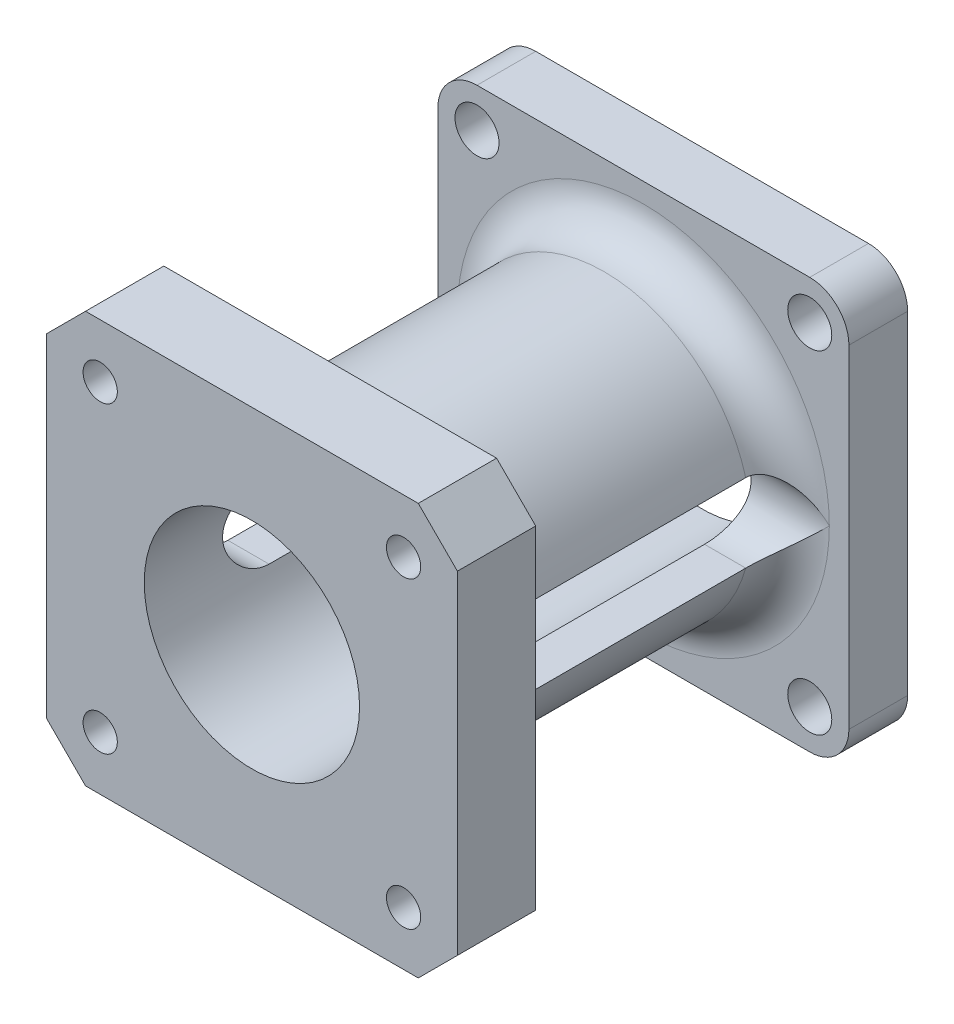
SolidWorks part; units mm, degrees
ref_plane "Alzado" through (0, 0, 0) normal (0, 0, 1) x (1, 0, 0)
ref_plane "Planta" through (0, 0, 0) normal (0, 1, 0) x (1, 0, 0)
ref_plane "Vista lateral" through (0, 0, 0) normal (1, 0, 0) x (0, 0, -1)
sketch "Croquis1" plane through (0, 0, 0) normal (0, 0, 1) x (1, 0, 0)
  line L1 (-21, 21) -> (21, 21)
  line L2 (-21, 21) -> (-21, -21)
  line L3 (-21, -21) -> (21, -21)
  line L4 (21, 21) -> (21, -21)
  line L5 (-21, 21) -> (21, -21) construction
  line L6 (-21, -21) -> (21, 21) construction
  point P0 (0, 0)
  dimension "D1" = 42
  dimension "D2" = 42
extrude "Saliente-Extruir1" add sketch "Croquis1" along normal blind 6
sketch "Croquis2" plane through (0, 0, 6) normal (0, 0, 1) x (1, 0, 0)
  circle A0 centre (0, 0) radius 15
  dimension "D1" = 30
extrude "Saliente-Extruir2" add sketch "Croquis2" along normal blind 32
sketch "Croquis3" plane through (0, 0, 38) normal (0, 0, 1) x (1, 0, 0)
  line L1 (-21, 21) -> (21, 21)
  line L2 (-21, 21) -> (-21, -21)
  line L3 (-21, -21) -> (21, -21)
  line L4 (21, 21) -> (21, -21)
  line L5 (-21, 21) -> (21, -21) construction
  line L6 (-21, -21) -> (21, 21) construction
  point P0 (0, 0)
  dimension "D1" = 42
  dimension "D2" = 42
extrude "Saliente-Extruir3" add sketch "Croquis3" along normal blind 8
sketch "Croquis4" plane through (0, 0, 46) normal (0, 0, 1) x (1, 0, 0)
  circle A0 centre (0, 0) radius 11
  dimension "D1" = 22
extrude "Cortar-Extruir1" cut sketch "Croquis4" against normal through all
sketch "Croquis5" plane through (0, 0, 46) normal (0, 0, 1) x (1, 0, 0)
  line L1 (-15.5, 15.5) -> (15.5, 15.5) construction
  line L2 (-15.5, 15.5) -> (-15.5, -15.5) construction
  line L3 (-15.5, -15.5) -> (15.5, -15.5) construction
  line L4 (15.5, 15.5) -> (15.5, -15.5) construction
  line L5 (-15.5, 15.5) -> (15.5, -15.5) construction
  line L6 (-15.5, -15.5) -> (15.5, 15.5) construction
  circle A0 centre (15.5, 15.5) radius 1.75
  circle A1 centre (-15.5, 15.5) radius 1.75
  circle A2 centre (-15.5, -15.5) radius 1.75
  circle A3 centre (15.5, -15.5) radius 1.75
  point P0 (0, 0)
  dimension "D3" = 3.5
  dimension "D4" = 3.5
  dimension "D5" = 3.5
  dimension "D6" = 3.5
  dimension "D1" = 31
  dimension "D2" = 31
extrude "Cortar-Extruir2" cut sketch "Croquis5" against normal blind 10
chamfer "Chaflán1" distance 4 angle 45 4 edges at (21, -21, 42) (-21, -21, 42) (-21, 21, 42) (21, 21, 42)
fillet "Redondeo1" radius 4 2 edges at (15, 0, 38) (15, 0, 6)
sketch "Croquis6" plane through (0, 0, 0) normal (0, 0, -1) x (-1, 0, 0)
  line L1 (17, 17) -> (-17, 17) construction
  line L2 (17, 17) -> (17, -17) construction
  line L3 (17, -17) -> (-17, -17) construction
  line L4 (-17, 17) -> (-17, -17) construction
  line L5 (17, 17) -> (-17, -17) construction
  line L6 (17, -17) -> (-17, 17) construction
  circle A0 centre (17, 17) radius 2.25
  circle A1 centre (17, -17) radius 2.25
  circle A2 centre (-17, -17) radius 2.25
  circle A3 centre (-17, 17) radius 2.25
  point P0 (0, 0)
  dimension "D3" = 4.5
  dimension "D4" = 4.5
  dimension "D5" = 4.5
  dimension "D6" = 4.5
  dimension "D1" = 34
  dimension "D2" = 34
extrude "Cortar-Extruir3" cut sketch "Croquis6" against normal blind 10
fillet "Redondeo2" radius 4 4 edges at (21, 21, 3) (21, -21, 3) (-21, 21, 3) (-21, -21, 3)
sketch "Croquis7" plane through (0, 0, 0) normal (1, 0, 0) x (0, 0, -1)
  line L0 (0, 0) -> (-46, 0) construction
  line L1 (-46, -17) -> (-46, 17) construction
  line L2 (-34, 0) -> (-10, 0) construction
  line L3 (-34, -15) -> (-34, 15) construction
  line L4 (-10, 15) -> (-10, -15) construction
  line L5 (-34, 4) -> (-10, 4)
  line L6 (-34, -4) -> (-10, -4)
  arc A0 (-34, 4) -> (-34, -4) centre (-34, 0) ccw
  arc A1 (-10, -4) -> (-10, 4) centre (-10, 0) ccw
  point P11 (-22, 0)
  dimension "D1" = 4
extrude "Cortar-Extruir4" cut sketch "Croquis7" against normal through all and the other way through all
sketch "Croquis8" plane through (0, 21, 0) normal (0, 1, 0) x (1, 0, 0)
  line L0 (17, -1.4453) -> (-17, -1.4453) construction
  line L1 (17, -6) -> (17, 0) construction
  line L2 (-17, 0) -> (-17, -6) construction
  text T0 "FRONT" font "Arial" height 3.5
